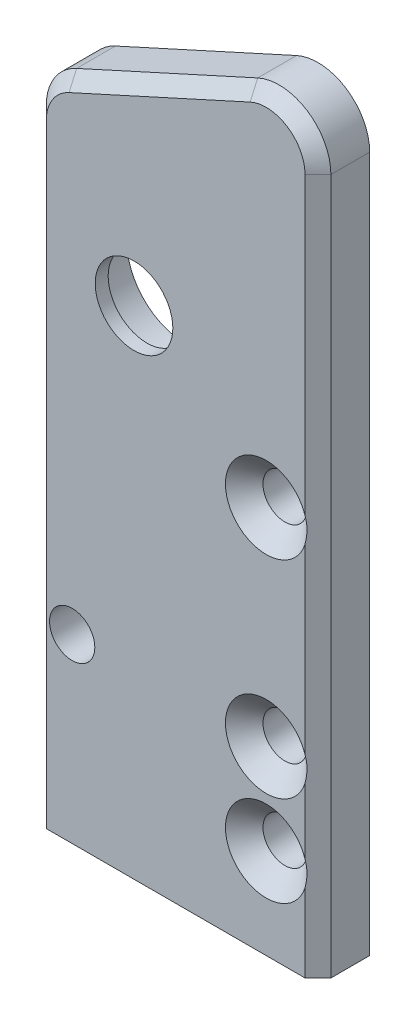
SolidWorks part; units mm, degrees
ref_plane "Plano frontal" through (0, 0, 0) normal (0, 0, 1) x (1, 0, 0)
ref_plane "Plano superior" through (0, 0, 0) normal (0, 1, 0) x (1, 0, 0)
ref_plane "Plano direito" through (0, 0, 0) normal (1, 0, 0) x (0, 0, -1)
sketch "Esboço1" plane through (0, 0, 0) normal (0, 0, 1) x (1, 0, 0)
  line L0 (0, 0) -> (22, 0)
  line L1 (22, 0) -> (22, 60)
  line L2 (22, 60) -> (0, 50)
  line L3 (0, 50) -> (0, 0)
  dimension "D1" = 50
  dimension "D2" = 60
  dimension "D3" = 22
extrude "Ressalto-extrusão1" add sketch "Esboço1" along normal blind 4
fillet "Filete1" radius 4 2 edges at (0, 50, 2) (22, 60, 2)
chamfer "Chanfro1" distance 1 angle 45 5 edges at (22, 26.894, 4) (20.1655, 57.1511, 4) (9.3448, 54.2476, 4) (0.6369, 49.5899, 4) (0, 23.7122, 4)
sketch "Esboço2" plane through (0, 0, 4) normal (0, 0, 1) x (1, 0, 0)
  line L0 (0, 0) -> (-10, 0) construction
  line L1 (-10, 0) -> (-10, 13) construction
  line L2 (-10, 13) -> (-41, 13) construction
  line L3 (-10, 13) -> (7.7809, 38.3937) construction
  line L4 (7.7809, 38.3937) -> (7.7809, 0) construction
  line L5 (1, 0) -> (21, 0) construction
  circle A0 centre (-10, 13) radius 31 construction
  dimension "D1" = 62
  dimension "D2" = 125
  dimension "D3" = 10
  dimension "D4" = 13
hole_wizard "Furo de diâmetro Ø6.0 (6)1" positions "3DSketch1" profile "Esboço3" hole size "Ø6.0" standard "ISO" end condition up to next
sketch3d "3DSketch1"
  point P0 (7.7809, 38.3937, 4)
sketch "Esboço3" plane through (7.7809, 38.3937, 4) normal (1, 0, 0) x (0, -1, 0)
  line L0 (0, 0) -> (0, 4)
  line L1 (0, 4) -> (3, 4)
  line L2 (3, 4) -> (3, 0)
  line L5 (3, 0) -> (0, 0)
  line L11 (0, -6.35) -> (0, 107.95) construction
  dimension "Thru Hole Dia." = 6
  dimension "Thru Hole Depth" = 4
sketch "Esboço6" plane through (0, 0, 4) normal (0, 0, 1) x (1, 0, 0)
  line L0 (18, 7) -> (18, 14) construction
  line L1 (1, 0) -> (21, 0) construction
  line L2 (22, 53.788) -> (22, 0) construction
  line L3 (18, 14) -> (3, 14) construction
  line L4 (0, 0) -> (0, 47.4243) construction
  point P0 (18, 7)
  point P1 (18, 14)
  dimension "D1" = 4
  dimension "D2" = 7
  dimension "D3" = 7
  dimension "D4" = 3
hole_wizard "Escareado para parafuso com cabeça escareada elevada de M31" positions "3DSketch3" profile "Esboço7" countersink size "M3" standard "ISO" end condition through all
sketch3d "3DSketch3"
  point P0 (18, 7, 4)
  point P3 (18, 14, 4)
sketch "Esboço7" plane through (18, 7, 4) normal (1, 0, 0) x (0, -1, 0)
  line L0 (0, 0) -> (0, 4)
  line L1 (0, 4) -> (1.7, 4)
  line L2 (1.7, 4) -> (1.7, 1.45)
  line L3 (1.7, 1.45) -> (3.15, 0)
  line L5 (3.15, 0) -> (0, 0)
  line L6 (-1.7, 1.45) -> (-3.15, 0) construction
  line L11 (0, -6.35) -> (0, 107.95) construction
  dimension "Thru Hole Dia." = 3.4
  dimension "Thru Hole Depth" = 4
  dimension "Near C'Sink Dia." = 6.3
  dimension "Near C'Sink Angle" = 90
sketch "Esboço8" plane through (0, 0, 0) normal (0, -1, 0) x (1, 0, 0)
  line L0 (0, 0) -> (0, 4) construction
  line L1 (0, 2) -> (22, 2) construction
  line L2 (22, 3) -> (22, 0) construction
  point P7 (8, 2)
  point P8 (4, 2)
  point P9 (12, 2)
  dimension "D1" = 4
  dimension "D2" = 4
  dimension "D3" = 4
  dimension "D4" = 4
hole_wizard "Broca de rosquear para tarraxa de M21" positions "3DSketch4" profile "Esboço9" hole size "M2" standard "ISO"
sketch3d "3DSketch4"
  point P3 (4, 0, 2)
  point P7 (12, 0, 2)
sketch "Esboço9" plane through (4, 0, 2) normal (1, 0, 0) x (0, 0, -1)
  line L0 (0, 0) -> (0, 10.4807)
  line L1 (0, 10.4807) -> (0.8, 10)
  line L2 (0.8, 10) -> (0.8, 0)
  line L5 (0.8, 0) -> (0, 0)
  line L10 (0, 10.4807) -> (-0.8, 10) construction
  line L11 (0, -6.35) -> (0, 107.95) construction
  dimension "Hole Dia." = 1.6
  dimension "Hole Depth" = 10
  dimension "Drill Angle" = 118
sketch "Esboço10" plane through (0, 0, 0) normal (0, 0, -1) x (-1, 0, 0)
  circle A0 centre (-7.7809, 38.3937) radius 3 construction
  circle A1 centre (-7.7809, 38.3937) radius 4.55
  point P0 (-7.7809, 38.3937)
  dimension "D1" = 9.1
sketch "Esboço14" plane through (0, 0, 4) normal (0, 0, 1) x (1, 0, 0)
  line L0 (22, 53.788) -> (22, 0) construction
  line L1 (0, 0) -> (22, 0) construction
  point P0 (18, 30)
  dimension "D1" = 4
  dimension "D2" = 30
hole_wizard "Escareado para parafuso com cabeça escareada chata de M31" positions "3DSketch6" profile "Esboço15" countersink size "M3" standard "ISO"
sketch3d "3DSketch6"
  point P0 (18, 30, 4)
sketch "Esboço15" plane through (18, 30, 4) normal (1, 0, 0) x (0, -1, 0)
  line L0 (0, 0) -> (0, 5.0215)
  line L1 (0, 5.0215) -> (1.7, 4)
  line L2 (1.7, 4) -> (1.7, 1.45)
  line L3 (1.7, 1.45) -> (3.15, 0)
  line L5 (3.15, 0) -> (0, 0)
  line L6 (-1.7, 1.45) -> (-3.15, 0) construction
  line L10 (0, 5.0215) -> (-1.7, 4) construction
  line L11 (0, -6.35) -> (0, 107.95) construction
  dimension "Hole Dia." = 3.4
  dimension "Hole Depth" = 4
  dimension "Near C'Sink Dia." = 6.3
  dimension "Near C'Sink Angle" = 90
  dimension "Drill Angle" = 118
extrude "Corte-extrusão1" cut sketch "Esboço10" against normal blind 3
hole_wizard "Furo de diâmetro Ø3.5 (3.5)1" positions "3DSketch7" profile "Esboço16" hole size "Ø3.5" standard "ISO" end condition through all
sketch3d "3DSketch7"
  point P0 (3, 14, 4)
sketch "Esboço16" plane through (3, 14, 4) normal (1, 0, 0) x (0, -1, 0)
  line L0 (0, 0) -> (0, 4)
  line L1 (0, 4) -> (1.75, 4)
  line L2 (1.75, 4) -> (1.75, 0)
  line L5 (1.75, 0) -> (0, 0)
  line L11 (0, -6.35) -> (0, 107.95) construction
  dimension "Thru Hole Dia." = 3.5
  dimension "Thru Hole Depth" = 4
